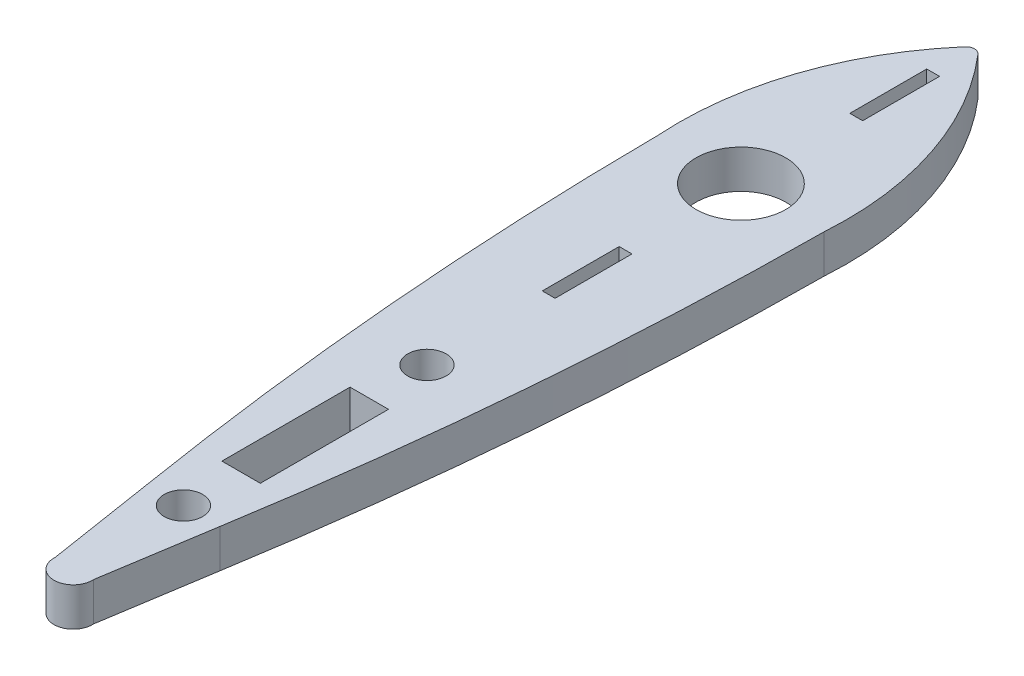
SolidWorks part; units mm, degrees
material "Cedro"
ref_plane "Plano frontal" through (0, 0, 0) normal (0, 0, 1) x (1, 0, 0)
ref_plane "Plano superior" through (0, 0, 0) normal (0, 1, 0) x (1, 0, 0)
ref_plane "Plano direito" through (0, 0, 0) normal (1, 0, 0) x (0, 0, -1)
sketch "Esboço1" plane through (0, 0, 0) normal (0, 1, 0) x (1, 0, 0)
  line L0 (-0.0431, -14.8771) -> (-0.5431, -14.8771)
  line L1 (-0.5431, -14.8771) -> (-0.5431, -8.8771)
  line L2 (-0.5431, -8.8771) -> (0.4569, -8.8771)
  line L3 (0.4569, -8.8771) -> (0.4569, -14.8771)
  line L4 (0.4569, -14.8771) -> (-0.0431, -14.8771)
  line L5 (0.4569, 15.1229) -> (-0.0431, 15.1229)
  line L6 (0.4569, 9.1229) -> (0.4569, 15.1229)
  line L7 (-0.5431, 9.1229) -> (0.4569, 9.1229)
  line L8 (-0.5431, 15.1229) -> (-0.5431, 9.1229)
  line L9 (-0.0431, 15.1229) -> (-0.5431, 15.1229)
  line L13 (-0.0431, -28.8771) -> (1.4569, -28.8771)
  line L14 (1.4569, -28.8771) -> (1.4569, -38.8771)
  line L15 (1.4569, -38.8771) -> (-0.0431, -38.8771)
  line L16 (-0.0431, -28.8771) -> (-1.5431, -28.8771)
  line L17 (-1.5431, -28.8771) -> (-1.5431, -38.8771)
  line L18 (-1.5431, -38.8771) -> (-0.0431, -38.8771)
  line L19 (-1.5431, -51.8771) -> (-2.8821, -43.3771)
  line L20 (1.4569, -51.8771) -> (2.7959, -43.3771)
  circle A0 centre (-0.0431, 0.1229) radius 3.5
  circle A1 centre (-0.0431, -24.3771) radius 1.5
  circle A2 centre (-0.0431, -43.3771) radius 1.5
  arc A3 (-6.5431, 0.1229) -> (-0.5431, 18.1229) centre (18.3299, 1.8319) cw
  arc A4 (6.4569, 0.1229) -> (0.4569, 18.1229) centre (-18.4162, 1.8319) ccw
  arc A5 (-0.5431, 18.1229) -> (0.4569, 18.1229) centre (-0.0431, 17.6744) cw
  arc A6 (-2.8821, -43.3771) -> (-6.5431, 0.1229) centre (275.4178, 1.9491) cw
  arc A7 (2.7959, -43.3771) -> (6.4569, 0.1229) centre (-275.504, 1.9491) ccw
  arc A8 (-1.5431, -51.8771) -> (1.4569, -51.8771) centre (-0.0431, -51.9759) ccw
extrude "Ressalto-extrusão1" add sketch "Esboço1" along normal blind 3
